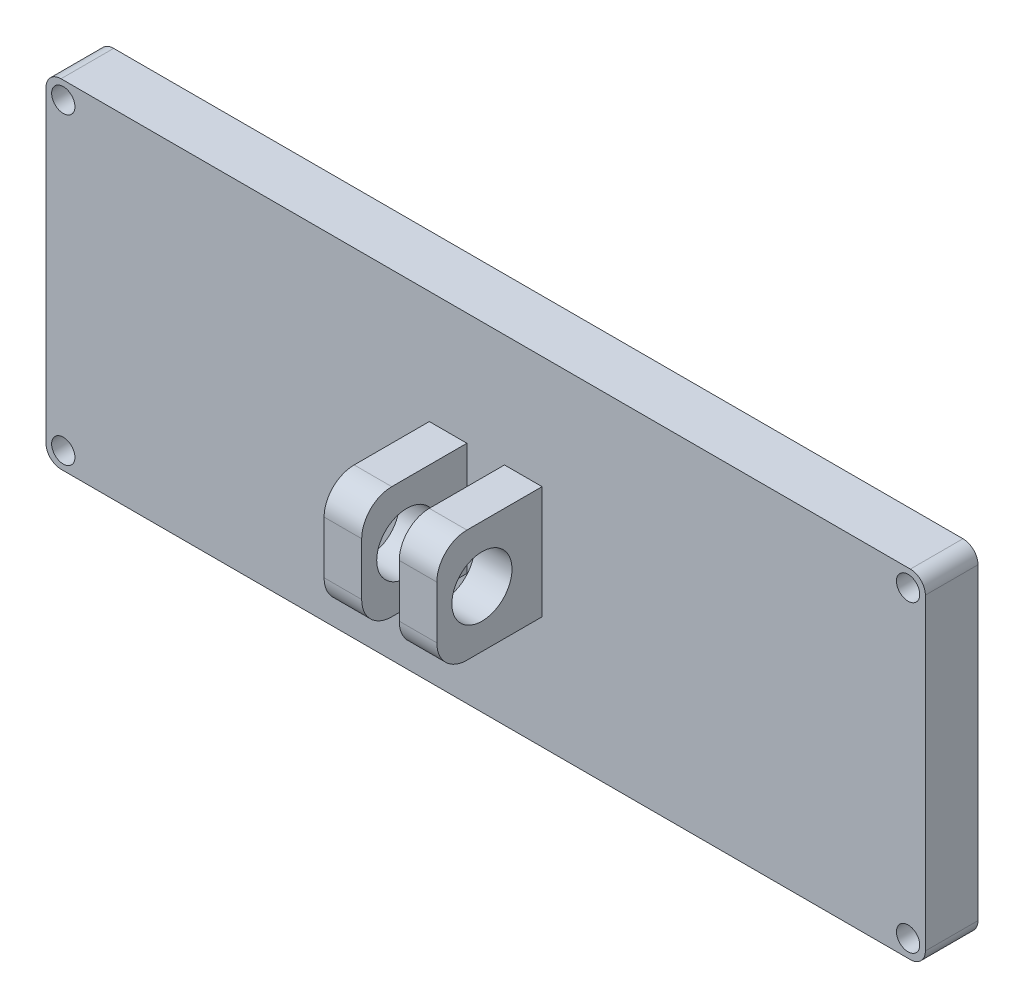
SolidWorks part; units mm, degrees
ref_plane "前视基准面" through (0, 0, 0) normal (0, 0, 1) x (1, 0, 0)
ref_plane "上视基准面" through (0, 0, 0) normal (0, 1, 0) x (1, 0, 0)
ref_plane "右视基准面" through (0, 0, 0) normal (1, 0, 0) x (0, 0, -1)
sketch "草图1" plane through (0, 0, 0) normal (0, 0, 1) x (1, 0, 0)
  line L1 (-58.5, -22.5) -> (58.5, -22.5)
  line L2 (-58.5, -22.5) -> (-58.5, 22.5)
  line L3 (-58.5, 22.5) -> (58.5, 22.5)
  line L4 (58.5, -22.5) -> (58.5, 22.5)
  line L5 (-58.5, -22.5) -> (58.5, 22.5) construction
  line L6 (-58.5, 22.5) -> (58.5, -22.5) construction
  point P0 (0, 0)
  dimension "D1" = 117
  dimension "D2" = 45
extrude "凸台-拉伸1" add sketch "草图1" along normal blind 7
fillet "圆角1" radius 2 4 edges at (-58.5, -22.5, 3.5) (58.5, -22.5, 3.5) (58.5, 22.5, 3.5) (-58.5, 22.5, 3.5)
sketch "草图2" plane through (0, 0, 0) normal (0, 0, -1) x (-1, 0, 0)
  line L1 (-54.25, -17.75) -> (54.25, -17.75)
  line L2 (-54.25, -17.75) -> (-54.25, 17.75)
  line L3 (-54.25, 17.75) -> (54.25, 17.75)
  line L4 (54.25, -17.75) -> (54.25, 17.75)
  line L5 (-54.25, -17.75) -> (54.25, 17.75) construction
  line L6 (-54.25, 17.75) -> (54.25, -17.75) construction
  point P0 (0, 0)
  dimension "D1" = 35.5
  dimension "D2" = 108.5
extrude "切除-拉伸1" cut sketch "草图2" against normal blind 5
sketch "草图3" plane through (0, 0, 0) normal (0, 0, -1) x (-1, 0, 0)
  line L0 (-56.5, 22.5) -> (56.5, 22.5) construction
  line L1 (-58.5, -20.5) -> (-58.5, 20.5) construction
  line L2 (3.85, 0) -> (-3.85, 0) construction
  line L3 (0, 3.85) -> (0, -3.85) construction
  circle A0 centre (-56.2, 20.2) radius 1.55
  circle A1 centre (-56.2, -20.2) radius 1.55
  circle A2 centre (56.2, -20.2) radius 1.55
  circle A3 centre (56.2, 20.2) radius 1.55
  dimension "D1" = 2.3
  dimension "D2" = 2.3
extrude "切除-拉伸2" cut sketch "草图3" against normal through all
sketch "草图6" plane through (0, 0, 7) normal (0, 0, 1) x (1, 0, 0)
  line L1 (7.5, -7.5) -> (-7.5, -7.5)
  line L2 (7.5, -7.5) -> (7.5, 7.5)
  line L3 (7.5, 7.5) -> (-7.5, 7.5)
  line L4 (-7.5, -7.5) -> (-7.5, 7.5)
  line L5 (7.5, -7.5) -> (-7.5, 7.5) construction
  line L6 (7.5, 7.5) -> (-7.5, -7.5) construction
  point P0 (0, 0)
  dimension "D1" = 15
  dimension "D2" = 15
extrude "凸台-拉伸2" add sketch "草图6" along normal blind 14
sketch "草图7" plane through (-7.5, 0, 0) normal (-1, 0, 0) x (0, 0, 1)
  line L0 (21, 7.5) -> (21, -7.5) construction
  circle A0 centre (15, 0) radius 4
  point P2 (11.9715, 0)
  dimension "D1" = 6
extrude "切除-拉伸3" cut sketch "草图7" against normal through all
fillet "圆角2" radius 4 2 edges at (0, -7.5, 21) (0, 7.5, 21)
sketch "草图8" plane through (0, 0, 7) normal (0, 0, 1) x (1, 0, 0)
  line L0 (7.5, 7.5) -> (-7.5, 7.5) construction
  line L1 (2.5, -7.5) -> (-2.5, -7.5)
  line L2 (2.5, -7.5) -> (2.5, 7.5)
  line L3 (2.5, 7.5) -> (-2.5, 7.5)
  line L4 (-2.5, -7.5) -> (-2.5, 7.5)
  line L5 (2.5, -7.5) -> (-2.5, 7.5) construction
  line L6 (2.5, 7.5) -> (-2.5, -7.5) construction
  point P0 (0, 0)
  dimension "D1" = 5
extrude "切除-拉伸4" cut sketch "草图8" along normal blind 20
sketch "草图9" plane through (0, 0, 5) normal (0, 0, -1) x (-1, 0, 0)
  line L0 (-54.25, -17.75) -> (54.25, -17.75) construction
  line L1 (-54.25, 17.75) -> (-34.25, 17.75)
  line L2 (-54.25, 17.75) -> (-54.25, -17.75)
  line L3 (-54.25, -17.75) -> (-34.25, -17.75)
  line L4 (-34.25, 17.75) -> (-34.25, -17.75)
  line L5 (54.25, 17.75) -> (34.25, 17.75)
  line L6 (54.25, 17.75) -> (54.25, -17.75)
  line L7 (54.25, -17.75) -> (34.25, -17.75)
  line L8 (34.25, 17.75) -> (34.25, -17.75)
  dimension "D1" = 0
  dimension "D2" = 20
  dimension "D3" = 0
  dimension "D4" = 20
extrude "凸台-拉伸3" add sketch "草图9" along normal blind 1.5
